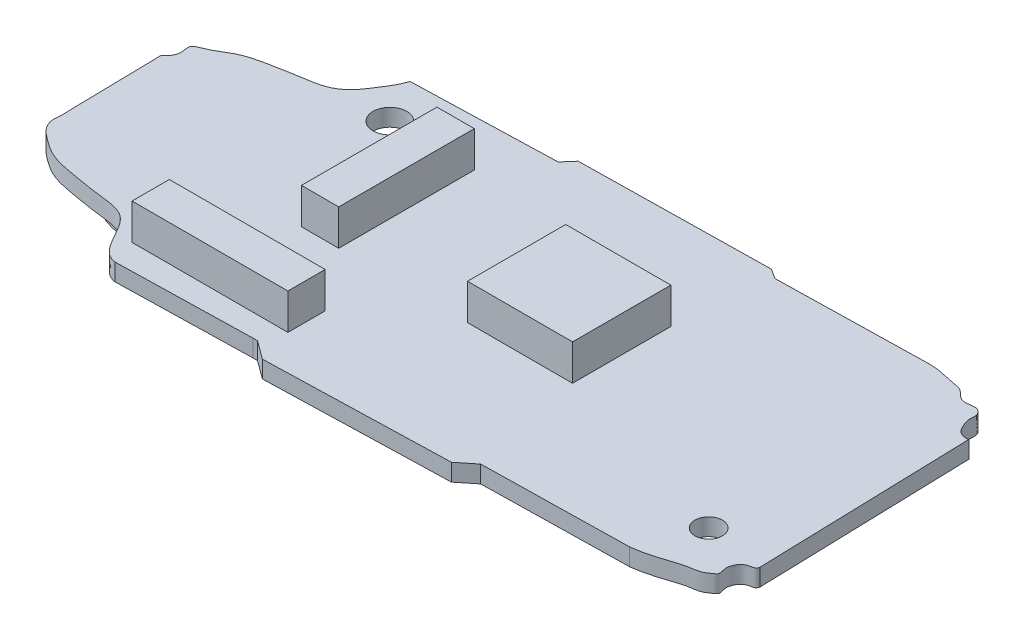
SolidWorks part; units mm, degrees
ref_plane "前视基准面" through (0, 0, 0) normal (0, 0, 1) x (1, 0, 0)
ref_plane "上视基准面" through (0, 0, 0) normal (0, 1, 0) x (1, 0, 0)
ref_plane "右视基准面" through (0, 0, 0) normal (1, 0, 0) x (0, 0, -1)
other "Configuration Table"
sketch "草图1" plane through (0, 0, 0) normal (0, 1, 0) x (1, 0, 0)
  line L0 (185.5083, 783.5795) -> (927.5417, 783.5795) construction
  line L1 (105.8936, 53.2751) -> (106.5455, 54.0174)
  line L2 (120.4905, 53.7917) -> (119.8008, 54.2347)
  line L3 (120.3078, 31.4182) -> (121.4353, 32.3288)
  line L4 (105.8936, 31.9977) -> (106.207, 31.9977)
  line L5 (106.207, 31.9977) -> (107.4871, 31.0561)
  circle A0 centre (97.5607, 49.8717) radius 1.1779
  circle A1 centre (133.2451, 36.418) radius 0.9561
  spline S0 degree 1 poles (106.5455, 54.0174) (119.8008, 54.2347) knots 0 0 1 1
  spline S1 degree 1 poles (85.7571, 38.6616) (85.6123, 45.8325) knots 0 0 1 1
  spline S2 degree 1 poles (96.4773, 31.7804) (105.8936, 31.9977) knots 0 0 1 1
  spline S3 degree 1 poles (107.4871, 31.0561) (120.3078, 31.4182) knots 0 0 1 1
  spline S4 degree 1 poles (136.9675, 50.8304) (137.4021, 35.8367) knots 0 0 1 1
  spline S5 degree 1 poles (131.1471, 54.0174) (120.4905, 53.7917) knots 0 0 1 1
  spline S6 degree 1 poles (131.6389, 32.5192) (121.4353, 32.3288) knots 0 0 1 1
  spline S7 degree 1 poles (95.8651, 52.9705) (105.8936, 53.2751) knots 0 0 1 1
  spline S8 degree 3 poles (96.4773, 31.7804) (95.1194, 31.9791) (94.7683, 35.0252) (91.7555, 35.2584) (89.8163, 35.5949) (87.9723, 35.9392) (86.5053, 36.9518) (85.5659, 37.7238) (85.7571, 38.6616) knots 0 0 0 0 0.292441 0.436631 0.610009 0.740354 0.839145 1 1 1 1
  spline S9 degree 3 poles (95.8651, 52.9705) (95.6994, 52.414) (95.1706, 51.625) (94.4782, 50.5092) (93.4295, 49.6731) (91.695, 49.4144) (89.9078, 49.1035) (88.2147, 48.6969) (87.2512, 47.989) (86.546, 47.7161) (85.9596, 47.4532) (86.2873, 46.5963) (85.9021, 46.0671) (85.6123, 45.8325) knots 0 0 0 0 0.125583 0.209642 0.288635 0.412114 0.58666 0.693684 0.791997 0.841791 0.868338 0.916807 1 1 1 1
  spline S10 degree 3 poles (131.1471, 54.0174) (131.7898, 53.9968) (132.271, 53.8062) (133.5914, 53.6431) (133.8642, 53.3324) (134.3785, 52.8845) (134.9066, 52.9642) (135.4365, 53.0467) (135.8578, 52.603) (135.6995, 52.022) (135.9157, 51.5404) (136.1803, 50.942) (136.6731, 50.7587) (136.9675, 50.8304) knots 0 0 0 0 0.18873 0.316316 0.403184 0.474448 0.548055 0.606941 0.678492 0.743591 0.828921 0.879784 1 1 1 1
  spline S11 degree 3 poles (131.6389, 32.5192) (132.2898, 32.5912) (133.3999, 32.8911) (134.7193, 33.3724) (135.6793, 33.4557) (136.0696, 33.7775) (136.4659, 34.019) (136.2103, 34.4949) (136.3091, 34.9306) (136.493, 35.3072) (136.9119, 35.6013) (137.3551, 35.5506) (137.4021, 35.8367) knots 0 0 0 0 0.265051 0.461165 0.575033 0.635407 0.669814 0.743469 0.801325 0.851395 0.909102 1 1 1 1
  dimension "D1" = 15
extrude "凸台-拉伸1" add sketch "草图1" along normal blind 1.2
sketch "草图2" plane through (0, 1.2, 0) normal (0, 1, 0) x (1, 0, 0)
  line L1 (100.8567, 49.8621) -> (103.4557, 49.8621)
  line L2 (100.8567, 49.8621) -> (100.8567, 40.4111)
  line L3 (100.8567, 40.4111) -> (103.4557, 40.4111)
  line L4 (103.4557, 49.8621) -> (103.4557, 40.4111)
  line L5 (95.8949, 36.1582) -> (106.7635, 36.1582)
  line L6 (95.8949, 36.1582) -> (95.8949, 33.5592)
  line L7 (95.8949, 33.5592) -> (106.7635, 33.5592)
  line L8 (106.7635, 36.1582) -> (106.7635, 33.5592)
  line L9 (112.4341, 47.263) -> (119.7585, 47.263)
  line L10 (112.4341, 47.263) -> (112.4341, 40.4111)
  line L11 (112.4341, 40.4111) -> (119.7585, 40.4111)
  line L12 (119.7585, 47.263) -> (119.7585, 40.4111)
extrude "凸台-拉伸2" add sketch "草图2" along normal blind 2.5
sketch "草图3" plane through (0, 0, 0) normal (0, -1, 0) x (-1, 0, 0)
  line L1 (-113.7863, 38.2898) -> (-119.45, 38.2898)
  line L2 (-113.7863, 38.2898) -> (-113.7863, 46.5182)
  line L3 (-113.7863, 46.5182) -> (-119.45, 46.5182)
  line L4 (-119.45, 38.2898) -> (-119.45, 46.5182)
  line L5 (-121.1598, 41.0682) -> (-123.9383, 41.0682)
  line L6 (-121.1598, 41.0682) -> (-121.1598, 44.4878)
  line L7 (-121.1598, 44.4878) -> (-123.9383, 44.4878)
  line L8 (-123.9383, 41.0682) -> (-123.9383, 44.4878)
  line L9 (-109.0844, 41.0682) -> (-111.8628, 41.0682)
  line L10 (-109.0844, 41.0682) -> (-109.0844, 44.4878)
  line L11 (-109.0844, 44.4878) -> (-111.8628, 44.4878)
  line L12 (-111.8628, 41.0682) -> (-111.8628, 44.4878)
  circle A0 centre (-91.8795, 42.4574) radius 5.1693
extrude "凸台-拉伸3" add sketch "草图3" along normal blind 2.5
